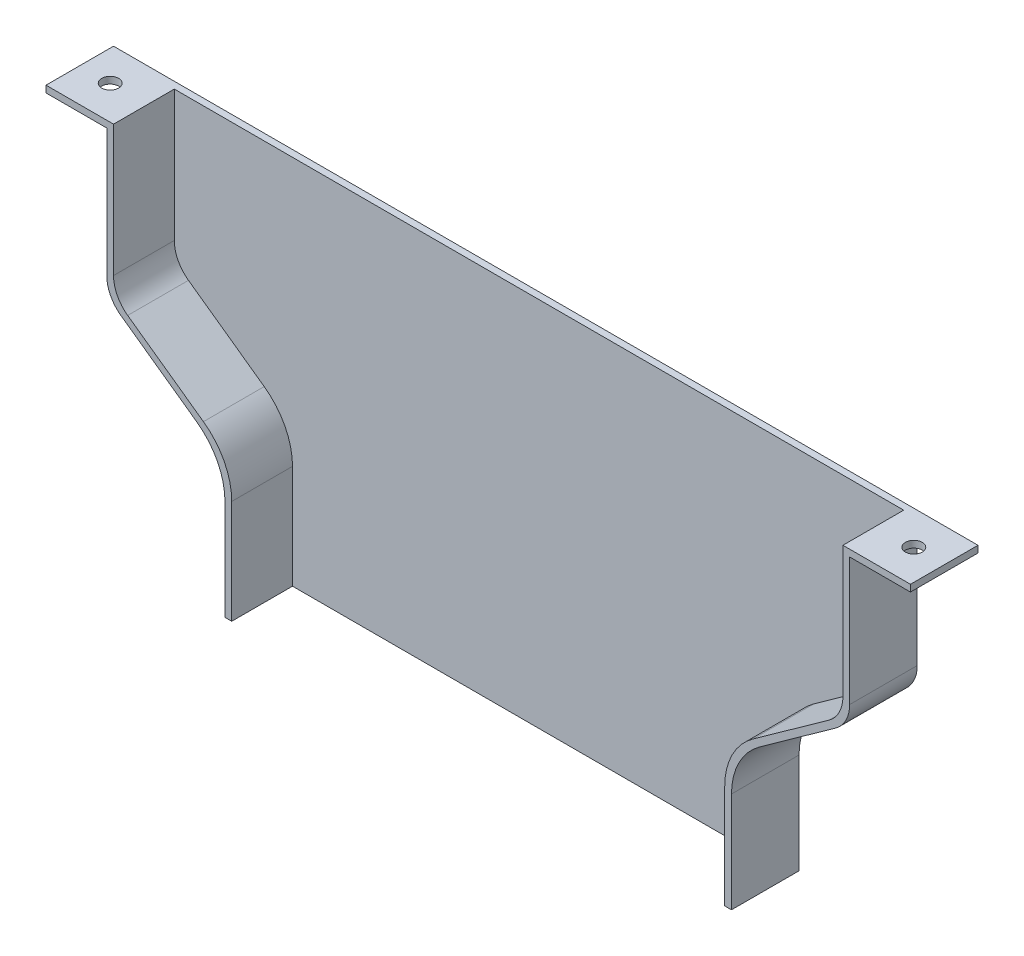
SolidWorks part; units mm, degrees
ref_plane "Plan de face" through (0, 0, 0) normal (0, 0, 1) x (1, 0, 0)
ref_plane "Plan de dessus" through (0, 0, 0) normal (0, 1, 0) x (1, 0, 0)
ref_plane "Plan de droite" through (0, 0, 0) normal (1, 0, 0) x (0, 0, -1)
sketch "Esquisse1" plane through (0, 0, 0) normal (0, 0, 1) x (1, 0, 0)
  line L0 (110, 110) -> (-110, 110)
  line L1 (-110, 110) -> (-110, 65)
  line L2 (-110, 65) -> (-75, 40)
  line L3 (-75, 40) -> (-75, 0)
  line L4 (-75, 0) -> (75, 0)
  line L5 (0, 83.9106) -> (0, 36.2829) construction
  line L6 (75, 40) -> (75, 0)
  line L7 (110, 65) -> (75, 40)
  line L8 (110, 110) -> (110, 65)
  point P10 (0, 0)
  point P13 (0, 110)
  dimension "D1" = 110
  dimension "D2" = 75
  dimension "D3" = 45
  dimension "D4" = 25
  dimension "D5" = 40
extrude "Boss.-Extru.1" add sketch "Esquisse1" along normal blind 20
sketch "Esquisse4" plane through (0, 0, 20) normal (0, 0, 1) x (1, 0, 0)
  line L0 (-108, 181.4856) -> (-108, 66.0292)
  line L1 (-73, -7.1297) -> (-73, 41.0292)
  line L3 (-108, 66.0292) -> (-73, 41.0292)
  line L4 (-110, 110) -> (-110, 65) construction
  line L10 (-75, 40) -> (-75, 0) construction
  line L13 (-110, 65) -> (-75, 40) construction
  line L14 (0, 34.3677) -> (0, 125.9982) construction
  line L15 (-73, -7.1297) -> (73, -7.1297)
  line L16 (-108, 181.4856) -> (108, 181.4856)
  line L17 (73, -7.1297) -> (73, 41.0292)
  line L18 (108, 66.0292) -> (73, 41.0292)
  line L19 (108, 181.4856) -> (108, 66.0292)
  point P16 (0, -7.1297)
  point P19 (0, 181.4856)
  dimension "D1" = 2
  dimension "D2" = 2
  dimension "D3" = 2
extrude "Enlèv. mat.-Extru.2" cut sketch "Esquisse4" against normal blind 18
fillet "Congé1" radius 20 4 edges at (75, 40, 10) (-75, 40, 10) (73, 41.0292, 11) (-73, 41.0292, 11)
fillet "Congé2" radius 10 4 edges at (108, 66.0292, 11) (-108, 66.0292, 11) (-110, 65, 10) (110, 65, 10)
sketch "Esquisse7" plane through (0, 110, 0) normal (0, 1, 0) x (1, 0, 0)
  line L0 (0, 24.5322) -> (0, -30.6115) construction
  line L5 (-108, 0) -> (-128, 0)
  line L6 (108, -20) -> (128, -20)
  line L7 (108, -20) -> (108, 0)
  line L8 (108, 0) -> (128, 0)
  line L13 (128, -20) -> (128, 0)
  line L14 (108, -20) -> (128, 0) construction
  line L15 (108, 0) -> (128, -20) construction
  line L16 (-128, -20) -> (-128, 0)
  line L17 (-108, -20) -> (-128, -20)
  line L18 (-108, -20) -> (-108, 0)
  point P4 (118, -10)
  dimension "D1" = 20
  dimension "D2" = 20
extrude "Boss.-Extru.2" add sketch "Esquisse7" against normal blind 2
sketch "Esquisse8" plane through (0, 108, 0) normal (0, -1, 0) x (1, 0, 0)
  line L0 (128, 20) -> (128, 0) construction
  line L1 (110, 20) -> (128, 20) construction
  line L2 (0, 14.9507) -> (0, 0) construction
  circle A0 centre (119, 10) radius 2.5
  circle A1 centre (-119, 10) radius 2.5
  point P4 (128, 10)
  point P7 (119, 20)
  dimension "D1" = 5
extrude "Enlèv. mat.-Extru.3" cut sketch "Esquisse8" against normal blind 10
